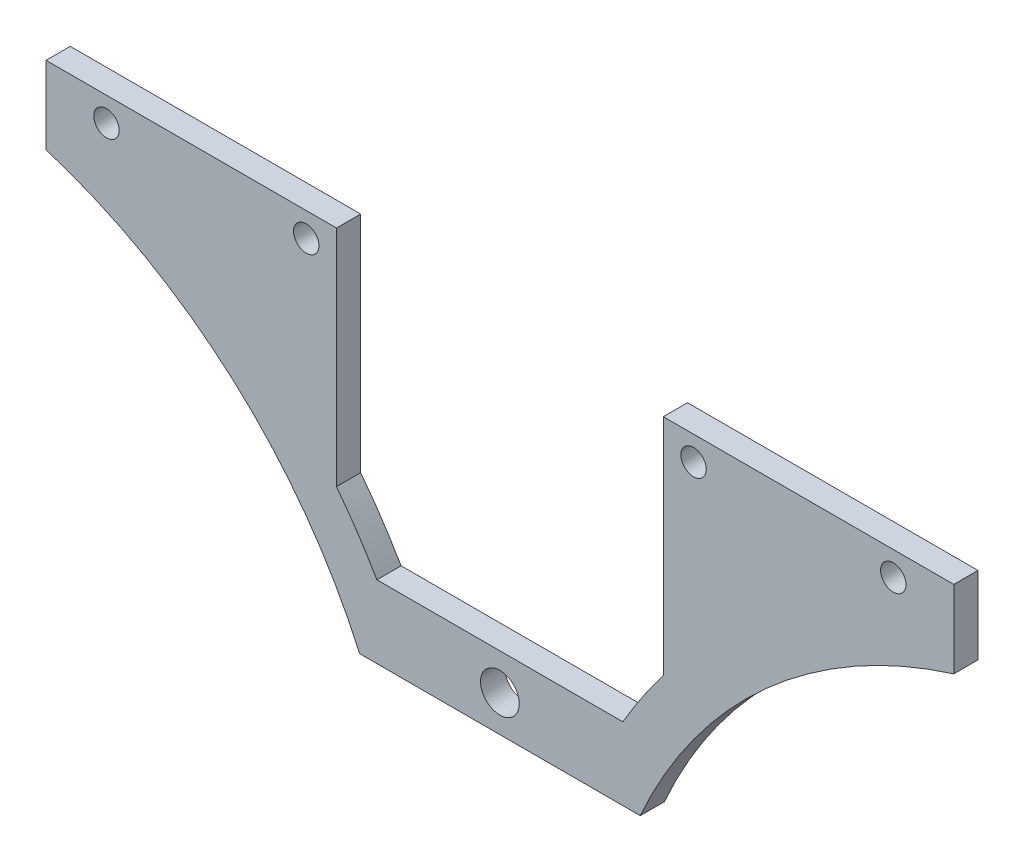
SolidWorks part; units mm, degrees
ref_plane "前视基准面" through (0, 0, 0) normal (0, 0, 1) x (1, 0, 0)
ref_plane "上视基准面" through (0, 0, 0) normal (0, 1, 0) x (1, 0, 0)
ref_plane "右视基准面" through (0, 0, 0) normal (1, 0, 0) x (0, 0, -1)
sketch "草图1" plane through (0, 0, 0) normal (0, 0, 1) x (1, 0, 0)
  line L5 (0, -55) -> (0, 55) construction
  line L7 (-10.1628, 3) -> (10.1628, 3)
  line L9 (13.5, 26.5) -> (13.5, 7.9955)
  line L10 (13.5, 26.5) -> (37.5, 26.5)
  line L11 (37.5, 26.5) -> (37.5, 20.0968)
  line L12 (-13.5, 26.5) -> (-37.5, 26.5)
  line L13 (-13.5, 26.5) -> (-13.5, 7.9955)
  line L14 (-37.5, 26.5) -> (-37.5, 20.0968)
  line L15 (-11.5943, -3) -> (11.5943, -3)
  arc A1 (37.5, 20.0968) -> (11.5943, -3) centre (50, -20) ccw
  arc A2 (-37.5, 20.0968) -> (-11.5943, -3) centre (-50, -20) cw
  arc A3 (13.5, 7.9955) -> (10.1628, 3) centre (50, -20) ccw
  arc A4 (-13.5, 7.9955) -> (-10.1628, 3) centre (-50, -20) cw
  circle A6 centre (0, 0) radius 1.6
  point P24 (0, 3)
extrude "凸台-拉伸1" add sketch "草图1" along normal blind 2
sketch "草图2" plane through (0, 0, 2) normal (0, 0, 1) x (1, 0, 0)
  circle A0 centre (-32.5, 24.5) radius 1.05
  circle A1 centre (-16, 24.5) radius 1.05
  circle A2 centre (16, 24.5) radius 1.05
  circle A3 centre (32.5, 24.5) radius 1.05
extrude "切除-拉伸1" cut sketch "草图2" against normal blind 10
